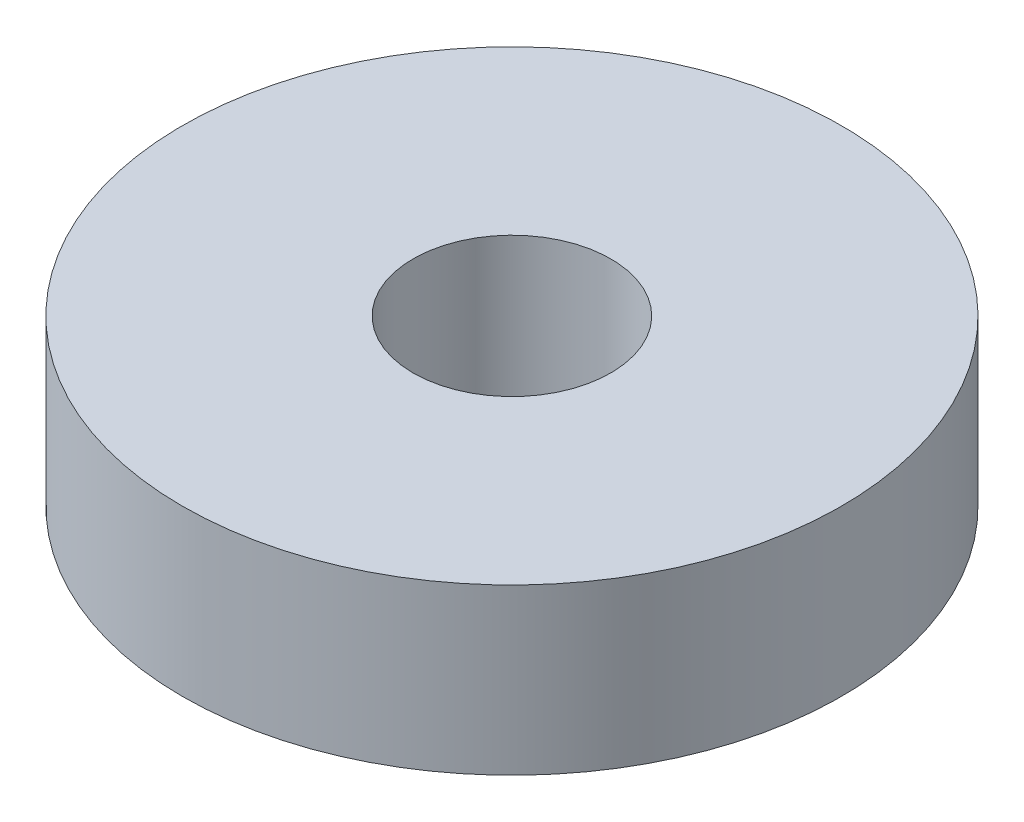
SolidWorks part; units mm, degrees
ref_plane "Plano frontal" through (0, 0, 0) normal (0, 0, 1) x (1, 0, 0)
ref_plane "Plano superior" through (0, 0, 0) normal (0, 1, 0) x (1, 0, 0)
ref_plane "Plano direito" through (0, 0, 0) normal (1, 0, 0) x (0, 0, -1)
sketch "Esboço1" plane through (0, 0, 0) normal (0, 1, 0) x (1, 0, 0)
  circle A0 centre (0, 0) radius 10
  circle A1 centre (0, 0) radius 3
  spline S0 degree 3 poles (0, 10) (-10.3379, 5.0883) (-7.3601, -6.5391) (0, -10) knots 0 0 0 0 1 1 1 1
  dimension "D1" = 20
  dimension "D2" = 6
extrude "Ressalto-extrusão1" add sketch "Esboço1" along normal blind 5 contours A0 S0 A1 | S0 A0
sketch "Esboço4" plane through (0, 5, 0) normal (0, 1, 0) x (1, 0, 0)
  circle A0 centre (0, 0) radius 10 construction
  arc A1 (0, 10) -> (0, -10) centre (0, 0) ccw
  spline S0 degree 3 poles (0, -10) (-6.1541, -3.9632) (-5.5876, 5.3537) (0, 10) knots 0 0 0 0 1 1 1 1
